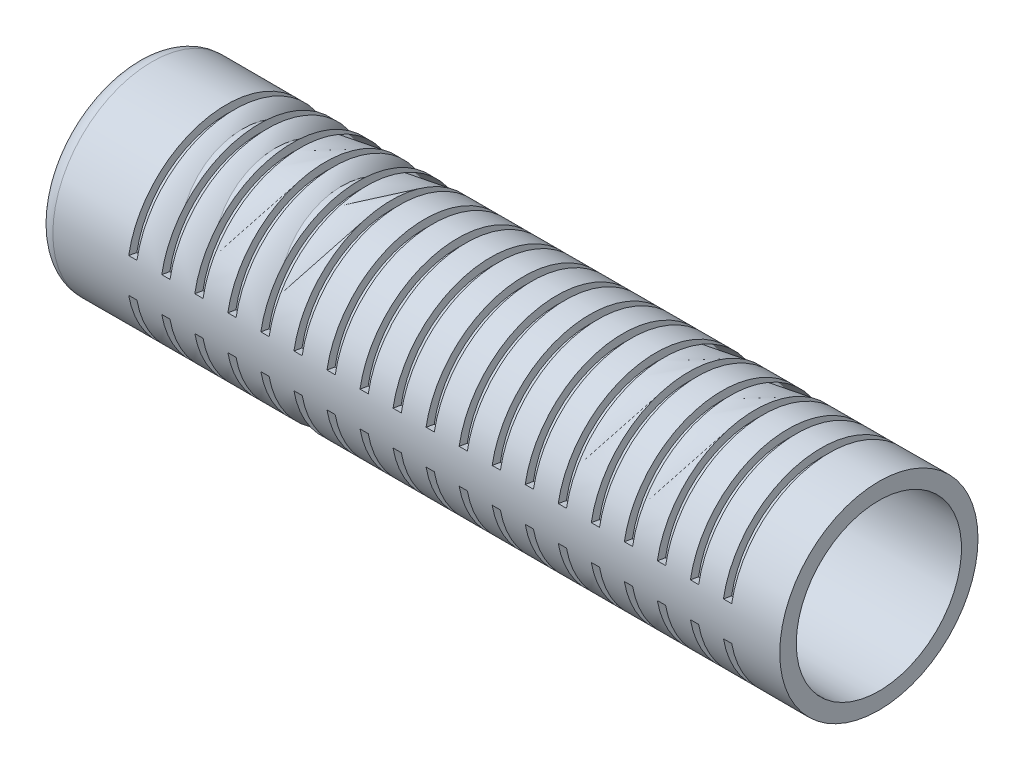
SolidWorks part; units mm, degrees
material "Rubber"
ref_plane "Front Plane" through (0, 0, 0) normal (0, 0, 1) x (1, 0, 0)
ref_plane "Top Plane" through (0, 0, 0) normal (0, 1, 0) x (1, 0, 0)
ref_plane "Right Plane" through (0, 0, 0) normal (1, 0, 0) x (0, 0, -1)
sketch "Sketch1" plane through (0, 0, 0) normal (0, 0, 1) x (1, 0, 0)
  line L0 (-57.15, 0) -> (57.15, 0) construction
  line L1 (-57.15, 15.24) -> (-57.15, -15.24) construction
  line L3 (-41.91, 15.24) -> (49.53, 15.24) construction
  line L4 (49.53, 15.24) -> (57.15, 15.24) construction
  line L5 (-57.15, 15.24) -> (-49.53, 15.24) construction
  line L6 (-49.53, 15.24) -> (-41.91, 15.24) construction
  point P11 (-57.15, 12.7)
  dimension "Length" = 114.3
  dimension "Textured Length" = 91.44
  dimension "OD" = 30.48
  dimension "For OD" = 25.4
sketch "Sketch2" plane through (0, 0, 0) normal (0, 0, 1) x (1, 0, 0)
  line L0 (-57.15, 12.7) -> (-57.15, 2.54)
  line L1 (-57.15, 2.54) -> (-54.61, 2.54)
  line L2 (-57.15, 15.24) -> (-57.15, -15.24) construction
  line L3 (-54.61, 2.54) -> (-54.61, 10.16)
  line L4 (-52.07, 12.7) -> (57.15, 12.7)
  line L5 (57.15, 12.7) -> (57.15, 15.24)
  line L6 (57.15, 15.24) -> (-54.61, 15.24)
  line L8 (-57.15, 0) -> (-57.15, 2.54) construction
  arc A0 (-54.61, 10.16) -> (-52.07, 12.7) centre (-52.07, 10.16) cw
  arc A1 (-57.15, 12.7) -> (-54.61, 15.24) centre (-54.61, 12.7) cw
  dimension "D1" = 2.54
revolve "Revolve1" add sketch "Sketch2" angle 360 about L0
sketch "Sketch3" plane through (0, 0, 0) normal (0, 0, 1) x (1, 0, 0)
  line L0 (48.26, 15.24) -> (49.53, 15.24)
  line L1 (-41.91, 15.24) -> (49.53, 15.24) construction
  line L2 (57.15, 12.7) -> (57.15, 15.24) construction
  line L3 (57.15, 13.97) -> (49.53, 13.97) construction
  line L5 (49.53, 15.24) -> (49.53, 13.97)
  line L6 (49.53, 13.97) -> (48.26, 13.97)
  line L7 (48.26, 13.97) -> (48.26, 15.24)
  dimension "D3" = 1.27
sketch "Sketch7" plane through (0, 0, 0) normal (1, 0, 0) x (0, 0, -1)
  line L0 (0, 15.24) -> (0, -15.24) construction
  line L3 (-15.0085, 2.6464) -> (0, 0) construction
  line L4 (0, 0) -> (15.0085, 2.6464) construction
  arc A0 (-13.7578, 2.4259) -> (13.7578, 2.4259) centre (0, 0) cw
  circle A1 centre (0, 0) radius 15.24 construction
  dimension "D1" = 10
sweep "Cut-Sweep1" cut profiles "Sketch3" path "Sketch7"
fillet "Fillet2" [suppressed] radius 0.635
fillet "Fillet3" [suppressed] radius 0.3175
mirror "Mirror1" about plane through (0, 0, 0) normal (0, 1, 0) of "Fillet2", "Fillet3", "Cut-Sweep1"
pattern_linear "LPattern2" count 19 spacing 5.08 along (-1, 0, 0) of "Cut-Sweep1", "Mirror1"
equation "\"OD@Sketch1\"=\"For OD@Sketch1\"*1.2"
equation "\"Textured Length@Sketch1\"=\"Length@Sketch1\"*.8"
equation "\"D1@Sketch2\"=(\"OD@Sketch1\"-\"For OD@Sketch1\")/2"
equation "\"D3@Sketch3\"=\"D1@Sketch2\"/2"
equation "\"D1@Fillet3\"=\"D1@Fillet2\"/2"
equation "\"D1@Fillet2\"=\"D3@Sketch3\"/2"
